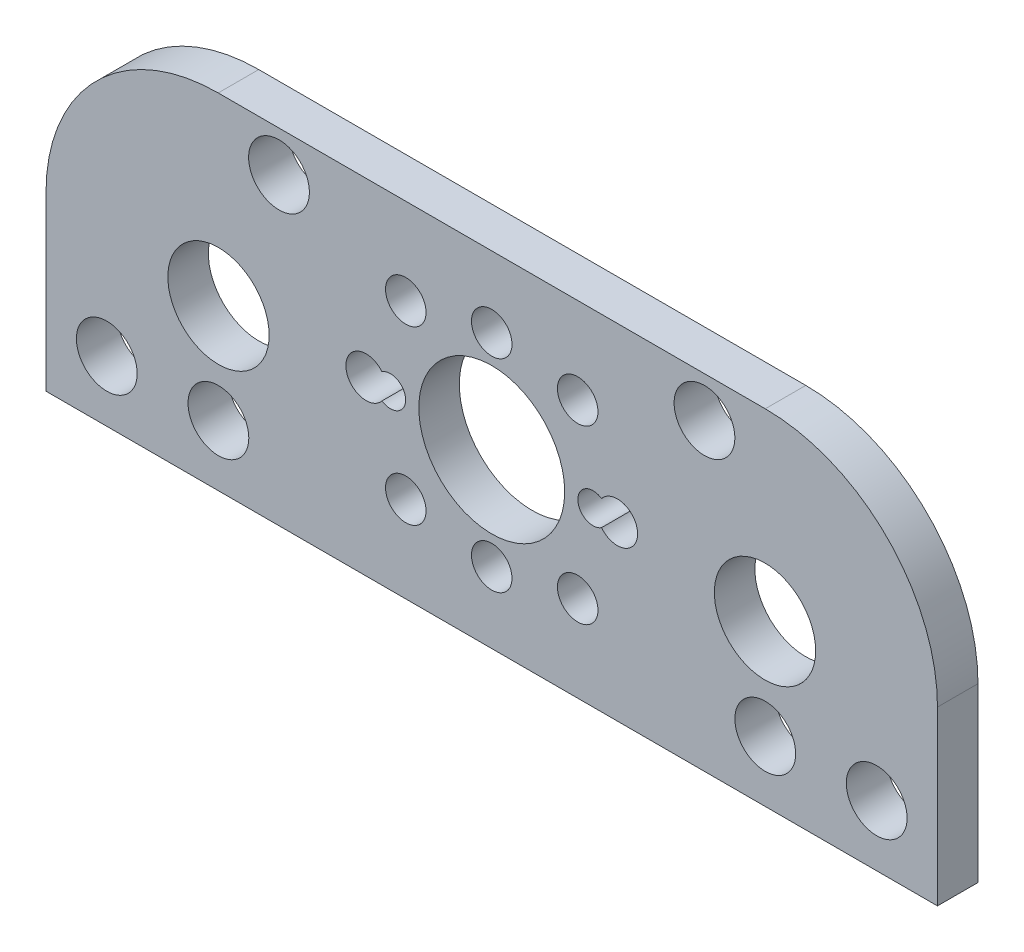
SolidWorks part; units mm, degrees
material "Thornel Mat VMA"
ref_plane "前视基准面" through (0, 0, 0) normal (0, 0, 1) x (1, 0, 0)
ref_plane "上视基准面" through (0, 0, 0) normal (0, 1, 0) x (1, 0, 0)
ref_plane "右视基准面" through (0, 0, 0) normal (1, 0, 0) x (0, 0, -1)
other "Configuration Table"
sketch "草图5" plane through (0, 0, 0) normal (0, 0, 1) x (1, 0, 0)
  circle A0 centre (0, 0) radius 8
sketch "草图6" plane through (0, 0, 0) normal (0, 0, 1) x (1, 0, 0)
  line L0 (-10.0496, 0) -> (9.8209, 0) construction
  line L1 (0, -6.8035) -> (0, 6.2826) construction
  line L2 (-4.2426, 4.2426) -> (0, 0) construction
  circle A0 centre (0, 0) radius 5 construction
  arc A1 (-5.4177, -0.6229) -> (-5.4177, 0.6229) centre (-5, 0) ccw
  arc A2 (5.4177, 0.6229) -> (5.4177, -0.6229) centre (5, 0) ccw
  circle A3 centre (0, 5) radius 1
  circle A4 centre (0, -5) radius 1
  arc A5 (-5.4177, 0.6229) -> (-5.4177, -0.6229) centre (-6.2, 0) ccw
  arc A6 (5.4177, -0.6229) -> (5.4177, 0.6229) centre (6.2, 0) ccw
  circle A7 centre (0, 0) radius 6 construction
  circle A8 centre (0, 0) radius 3.6
  circle A9 centre (-4.2426, 4.2426) radius 1
  circle A10 centre (4.2426, 4.2426) radius 1
  circle A11 centre (-4.2426, -4.2426) radius 1
  circle A12 centre (4.2426, -4.2426) radius 1
  circle A13 centre (0, 0) radius 4.25 construction
  dimension "D1" = 6.2
  dimension "D3" = 45
  dimension "D2" = 6.2
sketch "草图7" plane through (0, 0, 0) normal (0, 0, 1) x (1, 0, 0)
  circle A0 centre (0, 0) radius 13.5 construction
sketch "草图8" plane through (0, 0, 0) normal (0, 0, 1) x (1, 0, 0)
  circle A0 centre (-13.4867, -0.6) radius 2.5
  circle A1 centre (0, 0) radius 13.5 construction
  circle A2 centre (13.4867, -0.6) radius 2.5
  dimension "D1" = 0.6
  dimension "D2" = 0.6
sketch "草图10" plane through (0, 0, 0) normal (0, 0, 1) x (1, 0, 0)
  line L1 (-13.5, 8.5) -> (13.5, 8.5)
  line L2 (-22, 0) -> (-22, -8.5)
  line L3 (-22, -8.5) -> (22, -8.5)
  line L4 (22, 0) -> (22, -8.5)
  line L5 (-22, 8.5) -> (22, -8.5) construction
  line L6 (-22, -8.5) -> (22, 8.5) construction
  arc A2 (22, 0) -> (13.5, 8.5) centre (13.5, 0) ccw
  arc A3 (-22, 0) -> (-13.5, 8.5) centre (-13.5, 0) cw
  point P0 (0, 0)
  dimension "D3" = 8.5
  dimension "D1" = 17
  dimension "D2" = 44
extrude "凸台-拉伸1" add sketch "草图10" against normal blind 2
extrude "切除-拉伸1" cut sketch "草图6" against normal blind 2
extrude "切除-拉伸2" cut sketch "草图8" against normal blind 2
sketch "草图11" plane through (0, 0, 0) normal (0, 0, 1) x (1, 0, 0)
  line L1 (-22, -8.5) -> (-19, -8.5)
  line L2 (-22, -8.5) -> (-22, -5.5)
  line L3 (-22, -5.5) -> (-19, -5.5)
  line L4 (-19, -8.5) -> (-19, -5.5)
  line L5 (22, -8.5) -> (19, -8.5)
  line L6 (22, -8.5) -> (22, -5.5)
  line L7 (22, -5.5) -> (19, -5.5)
  line L8 (19, -8.5) -> (19, -5.5)
  dimension "D1" = 3
  dimension "D2" = 3
  dimension "D3" = 3
  dimension "D4" = 3
sketch "草图12" plane through (0, 0, 0) normal (0, 0, 1) x (1, 0, 0)
  line L0 (13.5, 8.5) -> (-13.5, 8.5) construction
  circle A0 centre (-19, -5.5) radius 1.5
  circle A1 centre (19, -5.5) radius 1.5
  circle A2 centre (-10.5, 6.5) radius 1.5
  circle A3 centre (10.5, 6.5) radius 1.5
  arc A4 (-13.5, 8.5) -> (-22, 0) centre (-13.5, 0) ccw construction
  circle A5 centre (-13.4907, -5.5) radius 1.5
  circle A6 centre (13.5, -5.5) radius 1.5
  dimension "D1" = 3
  dimension "D2" = 2
  dimension "D3" = 2
  dimension "D4" = 3
extrude "切除-拉伸3" cut sketch "草图12" against normal blind 10
